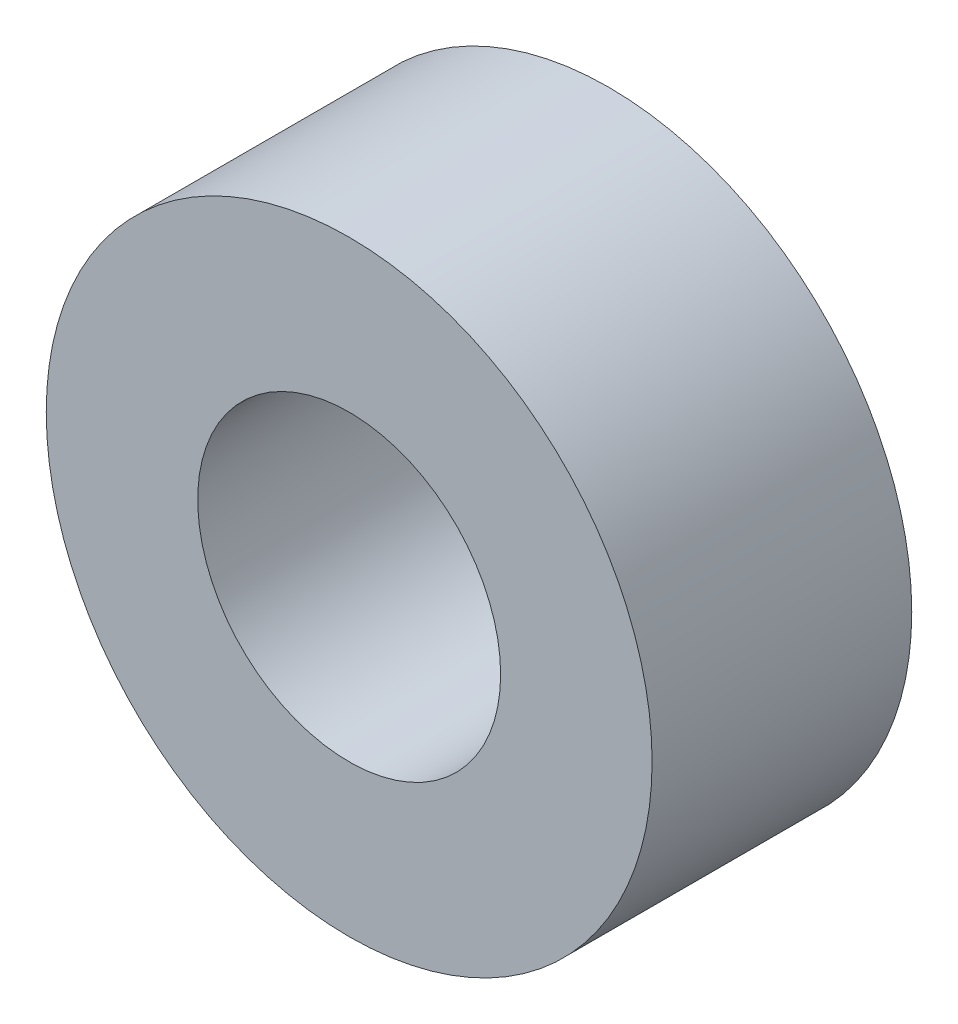
SolidWorks part; units mm, degrees
ref_plane "Спереди" through (0, 0, 0) normal (0, 0, 1) x (1, 0, 0)
ref_plane "Сверху" through (0, 0, 0) normal (0, 1, 0) x (1, 0, 0)
ref_plane "Справа" through (0, 0, 0) normal (1, 0, 0) x (0, 0, -1)
sketch "Эскиз1" plane through (0, 0, 0) normal (0, 0, 1) x (1, 0, 0)
  circle A0 centre (0, 0) radius 1.75
  circle A1 centre (0, 0) radius 3.5
  dimension "D1" = 3.5
  dimension "D2" = 7
extrude "Бобышка-Вытянуть1" add sketch "Эскиз1" along normal blind 3
